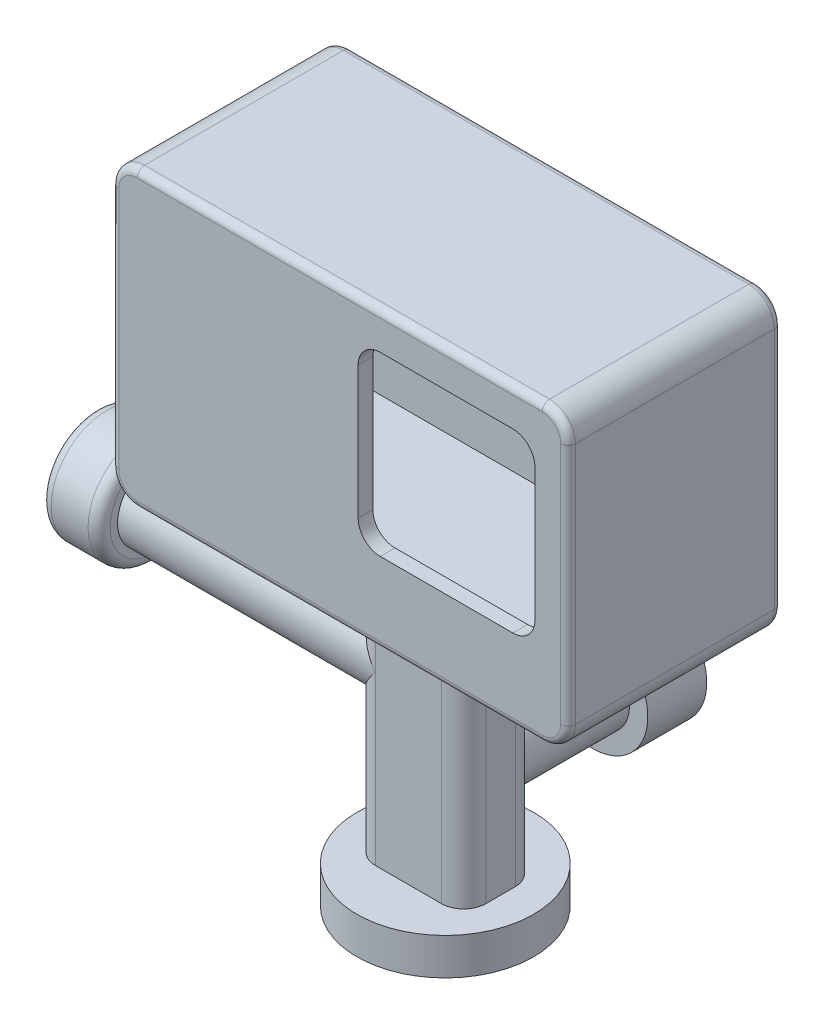
SolidWorks part; units mm, degrees
ref_plane "Front Plane" through (0, 0, 0) normal (0, 0, 1) x (1, 0, 0)
ref_plane "Top Plane" through (0, 0, 0) normal (0, 1, 0) x (1, 0, 0)
ref_plane "Right Plane" through (0, 0, 0) normal (1, 0, 0) x (0, 0, -1)
sketch "Sketch1" plane through (0, 0, 0) normal (0, 0, 1) x (1, 0, 0)
  line L4 (29.5, 80) -> (29.5, 47)
  line L5 (27.5, 45) -> (-27.5, 45)
  line L6 (-29.5, 47) -> (-29.5, 80)
  line L7 (-27.5, 82) -> (27.5, 82)
  line L8 (31, 80) -> (31, 47)
  line L9 (27.5, 43.5) -> (-27.5, 43.5)
  line L10 (-31, 47) -> (-31, 80)
  line L11 (-27.5, 83.5) -> (27.5, 83.5)
  arc A4 (29.5, 80) -> (27.5, 82) centre (27.5, 80) ccw
  arc A5 (27.5, 45) -> (29.5, 47) centre (27.5, 47) ccw
  arc A6 (-29.5, 47) -> (-27.5, 45) centre (-27.5, 47) ccw
  arc A7 (-27.5, 82) -> (-29.5, 80) centre (-27.5, 80) ccw
  arc A8 (27.5, 43.5) -> (31, 47) centre (27.5, 47) ccw
  arc A9 (-31, 47) -> (-27.5, 43.5) centre (-27.5, 47) ccw
  arc A10 (-27.5, 83.5) -> (-31, 80) centre (-27.5, 80) ccw
  arc A11 (31, 80) -> (27.5, 83.5) centre (27.5, 80) ccw
  dimension "D1" = 1.5
extrude "Boss-Extrude1" add sketch "Sketch1" against normal blind 27
sketch "Sketch2" plane through (0, 0, 0) normal (0, 0, 1) x (1, 0, 0)
  line L4 (27.5, 83.5) -> (-27.5, 83.5)
  line L5 (-31, 80) -> (-31, 47)
  line L6 (-27.5, 43.5) -> (27.5, 43.5)
  line L7 (31, 47) -> (31, 80)
  line L8 (27.5, 83.5) -> (-27.5, 83.5)
  line L9 (-31, 80) -> (-31, 47)
  line L10 (-27.5, 43.5) -> (27.5, 43.5)
  line L11 (31, 47) -> (31, 80)
  line L33 (23.5, 78.5) -> (5.5, 78.5)
  line L34 (2.5, 75.5) -> (2.5, 57.5)
  line L35 (5.5, 54.5) -> (23.5, 54.5)
  line L36 (26.5, 57.5) -> (26.5, 75.5)
  line L37 (23.5, 78.5) -> (5.5, 78.5)
  line L38 (2.5, 75.5) -> (2.5, 57.5)
  line L39 (5.5, 54.5) -> (23.5, 54.5)
  line L40 (26.5, 57.5) -> (26.5, 75.5)
  arc A4 (31, 80) -> (27.5, 83.5) centre (27.5, 80) ccw
  arc A5 (-27.5, 83.5) -> (-31, 80) centre (-27.5, 80) ccw
  arc A6 (-31, 47) -> (-27.5, 43.5) centre (-27.5, 47) ccw
  arc A7 (27.5, 43.5) -> (31, 47) centre (27.5, 47) ccw
  arc A8 (31, 80) -> (27.5, 83.5) centre (27.5, 80) ccw
  arc A9 (-27.5, 83.5) -> (-31, 80) centre (-27.5, 80) ccw
  arc A10 (-31, 47) -> (-27.5, 43.5) centre (-27.5, 47) ccw
  arc A11 (27.5, 43.5) -> (31, 47) centre (27.5, 47) ccw
  arc A36 (26.5, 75.5) -> (23.5, 78.5) centre (23.5, 75.5) ccw
  arc A37 (5.5, 78.5) -> (2.5, 75.5) centre (5.5, 75.5) ccw
  arc A38 (2.5, 57.5) -> (5.5, 54.5) centre (5.5, 57.5) ccw
  arc A39 (23.5, 54.5) -> (26.5, 57.5) centre (23.5, 57.5) ccw
  arc A40 (26.5, 75.5) -> (23.5, 78.5) centre (23.5, 75.5) ccw
  arc A41 (5.5, 78.5) -> (2.5, 75.5) centre (5.5, 75.5) ccw
  arc A42 (2.5, 57.5) -> (5.5, 54.5) centre (5.5, 57.5) ccw
  arc A43 (23.5, 54.5) -> (26.5, 57.5) centre (23.5, 57.5) ccw
  dimension "D1" = 0
  dimension "D2" = 0
extrude "Boss-Extrude2" add sketch "Sketch2" along normal blind 2
sketch "Sketch3" plane through (0, 43.5, 0) normal (0, -1, 0) x (1, 0, 0)
  line L0 (0, -27) -> (0, 2) construction
  line L1 (0.405, -16.7128) -> (-5, -153.9931) construction
  line L2 (-5.6504, 219.5) -> (0.4026, -13.4973) construction
  line L4 (-7.5, -7.3323) -> (7.5, -7.3323)
  line L5 (-7.5, -7.3323) -> (-7.5, -17.3323)
  line L6 (-7.5, -17.3323) -> (7.5, -17.3323)
  line L7 (7.5, -7.3323) -> (7.5, -17.3323)
  line L8 (-31, -12.3323) -> (31.0779, -12.3323) construction
  line L9 (-27.5, -27) -> (27.5, -27) construction
  line L10 (-27.5, 2) -> (27.5, 2) construction
  point P10 (-31, -12.5)
  point P11 (0, -27)
  point P16 (0, 2)
  dimension "D1" = 7.5
  dimension "D2" = 15
  dimension "D3" = 10
  dimension "D4" = 5
extrude "Boss-Extrude3" add sketch "Sketch3" along normal blind 40
sketch "Sketch4" plane through (0, 3.5, 0) normal (0, -1, 0) x (1, 0, 0)
  line L0 (-7.5, -12.3323) -> (0, -12.3323) construction
  line L1 (-7.5, -7.3323) -> (-7.5, -17.3323) construction
  line L2 (0, -12.3323) -> (0, -7.3323) construction
  line L3 (7.5, -7.3323) -> (-7.5, -7.3323) construction
  circle A0 centre (0, -12.3323) radius 12
  point P6 (0, 0)
  point P10 (0, 0)
extrude "Boss-Extrude4" add sketch "Sketch4" against normal blind 5
fillet "Fillet2" radius 3 4 edges at (7.5, 26, -7.3323) (-7.5, 26, -7.3323) (-7.5, 26, -17.3323) (7.5, 26, -17.3323)
sketch "Sketch5" plane through (-7.5, 0, 0) normal (-1, 0, 0) x (0, 0, 1)
  line L0 (-12.3323, 43.5) -> (-12.3323, 8.5) construction
  line L3 (-12.3323, 3.5) -> (-12.3323, 8.5) construction
  line L4 (-0.3323, 8.5) -> (-24.3323, 8.5) construction
  circle A1 centre (-12.3323, 31.2278) radius 5
  point P4 (0, 0)
  point P10 (0, 0)
extrude "Boss-Extrude5" add sketch "Sketch5" along normal blind 32 and the other way blind 10
sketch "Sketch6" plane through (-39.5, 0, 0) normal (-1, 0, 0) x (0, 0, 1)
  circle A1 centre (-12.3323, 31.2278) radius 7.5
extrude "Boss-Extrude6" add sketch "Sketch6" along normal blind 8
sketch "Sketch7" plane through (-31, 0, 0) normal (-1, 0, 0) x (0, 0, 1)
  line L0 (-12.5, 83.5) -> (-12.5, 43.5) construction
  line L1 (-27, 83.5) -> (2, 83.5) construction
  line L2 (-27, 43.5) -> (2, 43.5) construction
  circle A0 centre (-12.5, 71.5) radius 5
  circle A1 centre (-12.5, 56.5) radius 5
  dimension "D1" = 12
  dimension "D2" = 15
extrude "Boss-Extrude7" add sketch "Sketch7" along normal blind 5
sketch "Sketch8" plane through (0, 0, -27) normal (0, 0, -1) x (-1, 0, 0)
  line L8 (-29, 80) -> (-29, 47)
  line L9 (-27.5, 45.5) -> (27.5, 45.5)
  line L10 (29, 47) -> (29, 80)
  line L11 (27.5, 81.5) -> (-27.5, 81.5)
  line L12 (-29, 80) -> (-29, 47)
  line L13 (-27.5, 45.5) -> (27.5, 45.5)
  line L14 (29, 47) -> (29, 80)
  line L15 (27.5, 81.5) -> (-27.5, 81.5)
  arc A8 (-27.5, 81.5) -> (-29, 80) centre (-27.5, 80) ccw
  arc A9 (-29, 47) -> (-27.5, 45.5) centre (-27.5, 47) ccw
  arc A10 (27.5, 45.5) -> (29, 47) centre (27.5, 47) ccw
  arc A11 (29, 80) -> (27.5, 81.5) centre (27.5, 80) ccw
  arc A12 (-27.5, 81.5) -> (-29, 80) centre (-27.5, 80) ccw
  arc A13 (-29, 47) -> (-27.5, 45.5) centre (-27.5, 47) ccw
  arc A14 (27.5, 45.5) -> (29, 47) centre (27.5, 47) ccw
  arc A15 (29, 80) -> (27.5, 81.5) centre (27.5, 80) ccw
  dimension "D1" = 2
extrude "Boss-Extrude8" add sketch "Sketch8" against normal blind 1 separate body
fillet "Fillet3" radius 1 16 edges at (29.9749, 82.4749, 2) (31, 63.5, 2) (29.9749, 44.5251, 2) (0, 43.5, 2) (-29.9749, 44.5251, 2) (-31, 63.5, 2) (-29.9749, 82.4749, 2) (0, 83.5, 2) (31, 63.5, -27) (29.9749, 44.5251, -27) (0, 43.5, -27) (-29.9749, 44.5251, -27) (-31, 63.5, -27) (-29.9749, 82.4749, -27) (0, 83.5, -27) (29.9749, 82.4749, -27)
fillet "Fillet4" radius 1.5 2 edges at (-39.5, 31.2278, -4.8323) (-47.5, 31.2278, -4.8323)
fillet "Fillet5" radius 1 2 edges at (-36, 56.5, -7.5) (-36, 71.5, -7.5)
sketch "Sketch9" plane through (0, 0, -17.3323) normal (0, 0, -1) x (-1, 0, 0)
  line L0 (27.5, 43.5) -> (-27.5, 43.5) construction
  circle A0 centre (0, 19.5) radius 5
  dimension "D1" = 24
extrude "Boss-Extrude9" add sketch "Sketch9" along normal blind 15 and the other way blind 5
sketch "Sketch11" plane through (0, 0, -32.3323) normal (0, 0, -1) x (-1, 0, 0)
  circle A0 centre (0, 19.5) radius 7.5
extrude "Boss-Extrude10" add sketch "Sketch11" along normal blind 8
